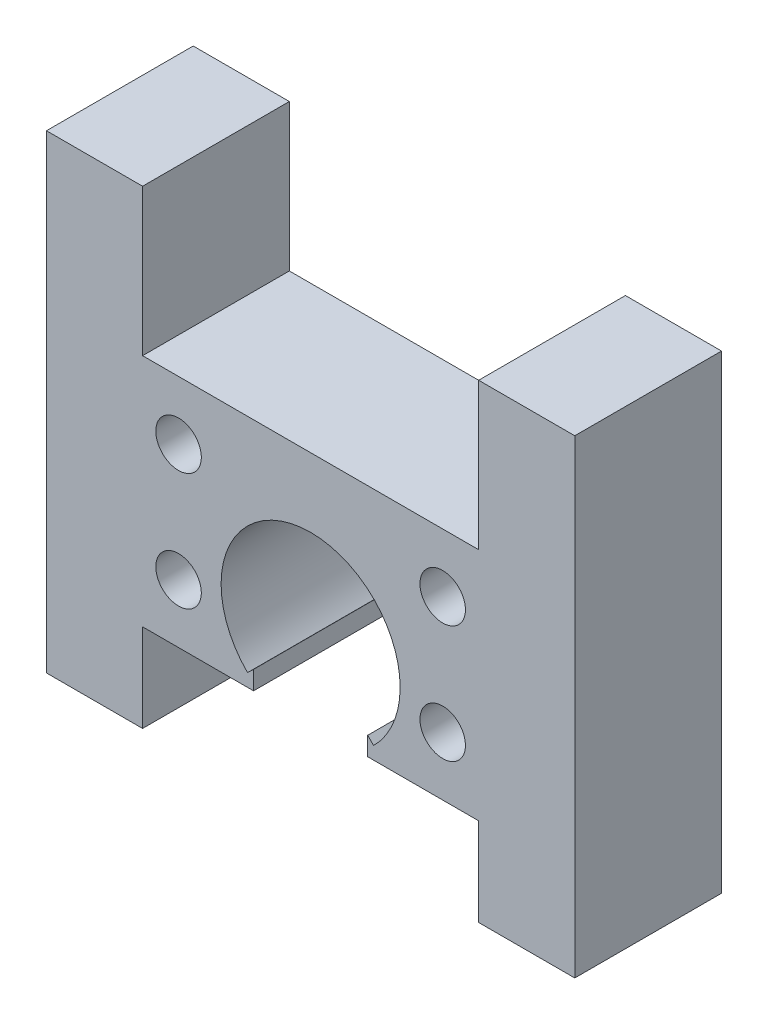
SolidWorks part; units mm, degrees
ref_plane "Płaszczyzna przednia" through (0, 0, 0) normal (0, 0, 1) x (1, 0, 0)
ref_plane "Płaszczyzna górna" through (0, 0, 0) normal (0, 1, 0) x (1, 0, 0)
ref_plane "Płaszczyzna prawa" through (0, 0, 0) normal (1, 0, 0) x (0, 0, -1)
sketch "Szkic1" plane through (0, 0, 0) normal (0, 0, 1) x (1, 0, 0)
  line L0 (71.503, 0) -> (35.503, 0)
  line L1 (71.503, 0) -> (71.503, -16)
  line L2 (35.503, 0) -> (35.503, -16)
  line L3 (71.503, -16) -> (35.503, -16)
  dimension "D1" = 36
  dimension "D2" = 16
extrude "Dodanie-wyciągnięcie1" add sketch "Szkic1" against normal blind 10
sketch "Szkic2" plane through (0, 0, -10) normal (0, 0, -1) x (-1, 0, 0)
  line L0 (-57.3914, -16) -> (-49.6145, -16)
  line L6 (-49.2044, -15.1281) -> (-49.6145, -14.7305)
  line L7 (-49.2044, -15.1281) -> (-49.6145, -14.7305)
  line L9 (-71.503, -16) -> (-63.9414, -16)
  line L10 (-57.3914, -22) -> (-57.3914, -14.7305)
  line L11 (-57.3914, -14.7305) -> (-57.7952, -15.1343)
  line L17 (-71.503, 0) -> (-71.503, -16)
  line L19 (-57.3914, -16) -> (-57.3914, -14.7305)
  line L20 (-57.3914, -14.7305) -> (-57.7952, -15.1343)
  line L22 (-49.6145, -14.7305) -> (-49.6145, -22)
  line L23 (-49.6145, -14.7305) -> (-49.6145, -16)
  line L24 (-43.0645, -16) -> (-35.503, -16)
  line L25 (-35.503, -16) -> (-35.503, 0)
  line L26 (-35.503, 0) -> (-43.0645, 0)
  line L300 (-63.9414, 0) -> (-71.503, 0)
  line L302 (-43.0645, 0) -> (-43.0645, 10)
  line L310 (-43.0645, 10) -> (-49.6145, 10)
  line L450 (-63.9414, -16) -> (-63.9414, -22)
  line L452 (-63.9414, -22) -> (-57.3914, -22)
  line L473 (-43.0645, -22) -> (-43.0645, -16)
  line L475 (-49.6145, -22) -> (-43.0645, -22)
  line L520 (-49.6145, 10) -> (-49.6145, 0)
  line L522 (-49.6145, 0) -> (-57.3914, 0)
  line L524 (-57.3914, 0) -> (-57.3914, 10)
  line L526 (-57.3914, 10) -> (-63.9414, 10)
  line L528 (-63.9414, 10) -> (-63.9414, 0)
  arc A1 (-49.2044, -15.1281) -> (-57.7952, -15.1343) centre (-53.503, -10.8) ccw
  arc A2 (-49.2044, -15.1281) -> (-57.7952, -15.1343) centre (-53.503, -10.8) ccw
  dimension "D1" = 0
extrude "Wytnij-wyciągnięcie1" cut sketch "Szkic2" against normal blind 10
sketch "Szkic3" plane through (0, 0, -10) normal (0, 0, -1) x (-1, 0, 0)
  circle A0 centre (-44.503, -12) radius 1.55 construction
  circle A1 centre (-44.503, -4) radius 1.55 construction
  circle A2 centre (-62.503, -12) radius 1.55 construction
  circle A3 centre (-62.503, -4) radius 1.55 construction
  circle A4 centre (-44.503, -12) radius 1.55
  circle A5 centre (-44.503, -4) radius 1.55
  circle A6 centre (-62.503, -12) radius 1.55
  circle A7 centre (-62.503, -4) radius 1.55
extrude "Wytnij-wyciągnięcie2" cut sketch "Szkic3" against normal through all
sketch "Szkic4" plane through (0, -16, 0) normal (0, -1, 0) x (1, 0, 0)
  line L1 (71.503, -10) -> (71.503, 0)
  line L3 (71.503, 0) -> (64.953, 0)
  line L4 (57.3914, 0) -> (71.503, 0) construction
  line L5 (64.953, 0) -> (64.953, -10)
  line L6 (57.3914, -10) -> (71.503, -10) construction
  line L7 (64.953, -10) -> (71.503, -10)
  line L12 (42.053, -10) -> (42.053, 0)
  line L13 (35.503, 0) -> (42.053, 0)
  line L14 (35.503, -10) -> (35.503, 0)
  line L15 (35.503, -10) -> (42.053, -10)
  dimension "D1" = 6.55
extrude "Dodanie-wyciągnięcie2" add sketch "Szkic4" along normal blind 6
sketch "Szkic5" plane through (0, 0, 0) normal (0, 1, 0) x (1, 0, 0)
  line L5 (42.053, 10) -> (42.053, 0) construction
  line L7 (35.503, 0) -> (35.503, 10) construction
  line L8 (64.953, 10) -> (71.503, 10)
  line L9 (71.503, 10) -> (71.503, 0)
  line L10 (71.503, 0) -> (64.953, 0)
  line L11 (64.953, 0) -> (64.953, 10)
  line L12 (35.503, 10) -> (42.053, 10)
  line L13 (42.053, 10) -> (42.053, 0)
  line L14 (42.053, 0) -> (35.503, 0)
  line L15 (35.503, 0) -> (35.503, 10)
  line L17 (71.503, 10) -> (35.503, 10) construction
  dimension "D1" = 0
extrude "Dodanie-wyciągnięcie3" add sketch "Szkic5" along normal blind 10
